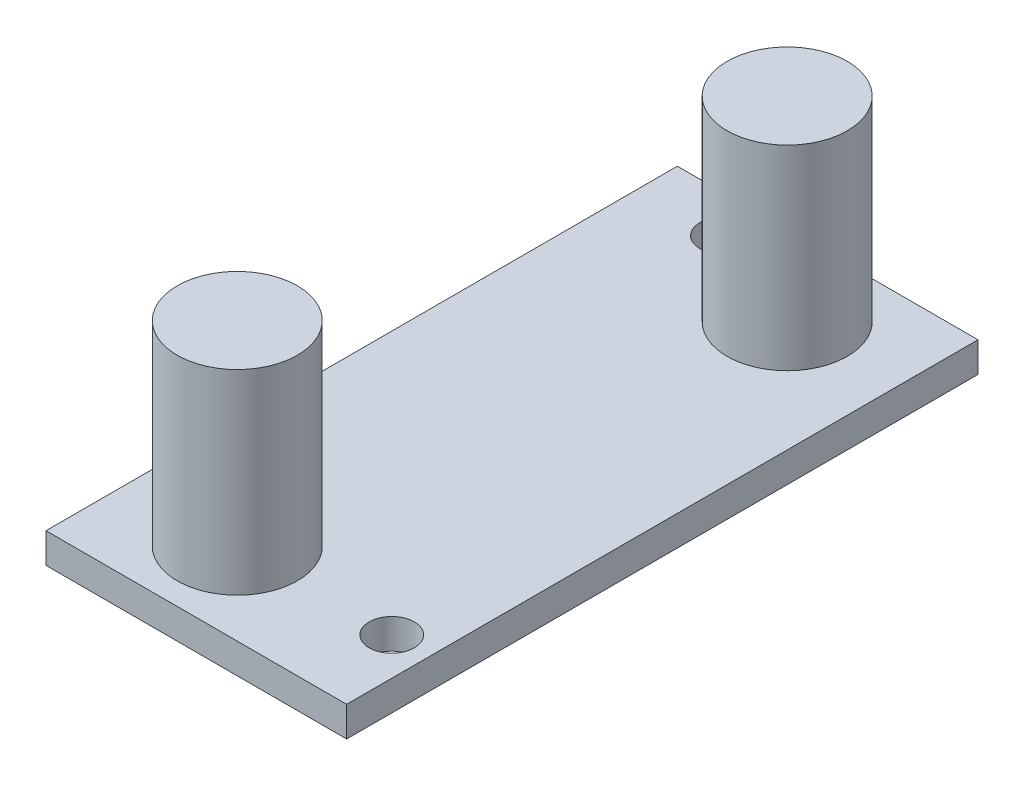
SolidWorks part; units mm, degrees
ref_plane "Front Plane" through (0, 0, 0) normal (0, 0, 1) x (1, 0, 0)
ref_plane "Top Plane" through (0, 0, 0) normal (0, 1, 0) x (1, 0, 0)
ref_plane "Right Plane" through (0, 0, 0) normal (1, 0, 0) x (0, 0, -1)
sketch "Sketch1" plane through (0, 0, 0) normal (0, 1, 0) x (1, 0, 0)
  line L1 (-10, -21) -> (10, -21)
  line L2 (-10, -21) -> (-10, 21)
  line L3 (-10, 21) -> (10, 21)
  line L4 (10, -21) -> (10, 21)
  line L5 (-10, -21) -> (10, 21) construction
  line L6 (-10, 21) -> (10, -21) construction
  point P0 (0, 0)
  dimension "D1" = 20
  dimension "D2" = 42
extrude "Boss-Extrude1" add sketch "Sketch1" along normal blind 2
sketch "Sketch2" plane through (0, 2, 0) normal (0, 1, 0) x (1, 0, 0)
  circle A0 centre (2.6112, 15.6961) radius 4
  circle A1 centre (-2.7484, -15.5259) radius 4
  dimension "D1" = 8
extrude "Boss-Extrude2" add sketch "Sketch2" along normal blind 13
sketch "Sketch3" plane through (0, 2, 0) normal (0, 1, 0) x (1, 0, 0)
  line L2 (10, -21) -> (10, 21) construction
  line L5 (-10, -21) -> (10, -21) construction
  line L6 (10, 21) -> (-10, 21) construction
  line L7 (-10, 21) -> (-10, -21) construction
  circle A0 centre (-4.5, 18.5) radius 1.5
  circle A1 centre (7.5, -15.5) radius 1.5
  dimension "D1" = 3
  dimension "D2" = 1
  dimension "D3" = 4
  dimension "D4" = 1
  dimension "D5" = 4
extrude "Cut-Extrude1" cut sketch "Sketch3" against normal through all
